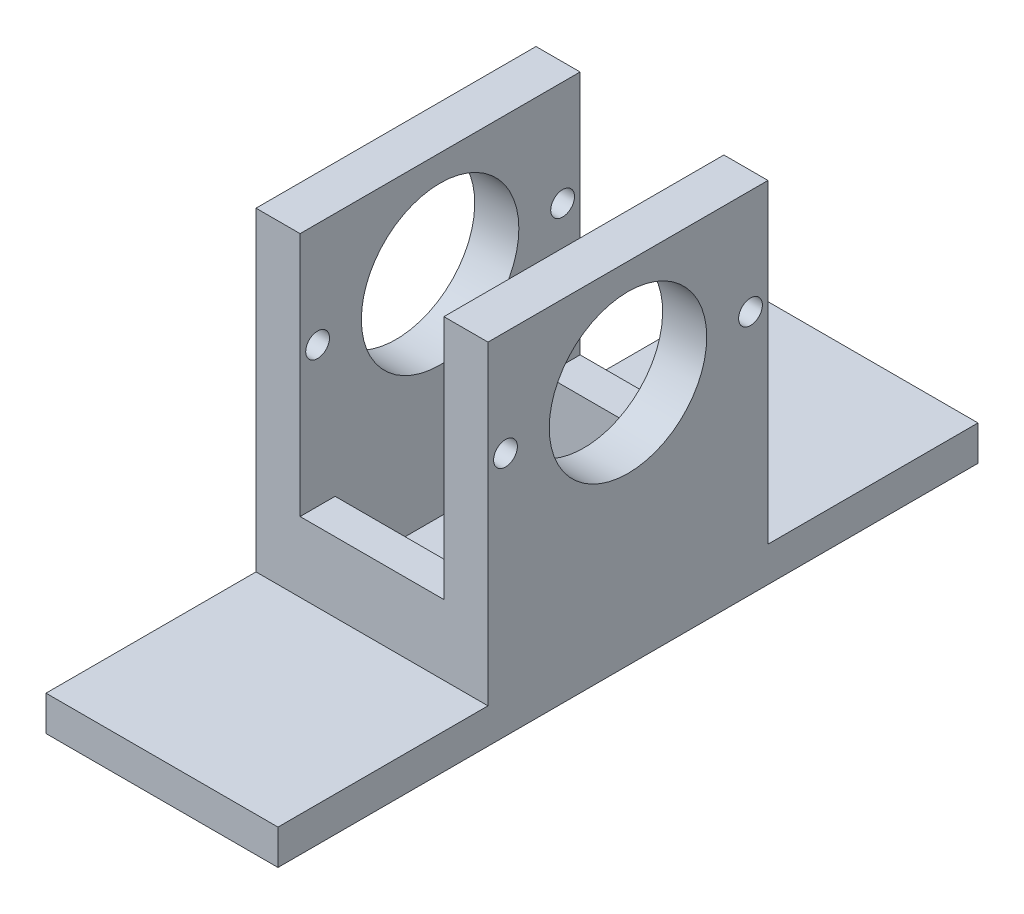
SolidWorks part; units mm, degrees
ref_plane "Front Plane" through (0, 0, 0) normal (0, 0, 1) x (1, 0, 0)
ref_plane "Top Plane" through (0, 0, 0) normal (0, 1, 0) x (1, 0, 0)
ref_plane "Right Plane" through (0, 0, 0) normal (1, 0, 0) x (0, 0, -1)
sketch "Sketch1" plane through (0, 0, 0) normal (0, 0, 1) x (1, 0, 0)
  line L0 (-21.0439, 0) -> (21.0439, 0)
  line L1 (-21.0439, 0) -> (-21.0439, 63.5)
  line L2 (21.0439, 0) -> (21.0439, 63.5)
  line L3 (-21.0439, 63.5) -> (-13.0429, 63.5)
  line L4 (-13.0429, 63.5) -> (-13.0429, 6.35)
  line L5 (-13.0429, 6.35) -> (13.0429, 6.35)
  line L6 (13.0429, 6.35) -> (13.0429, 63.5)
  line L7 (13.0429, 63.5) -> (21.0439, 63.5)
  point P3 (0, 0)
  dimension "D1" = 8.001
  dimension "D2" = 26.0858
  dimension "D3" = 6.35
  dimension "D4" = 57.15
extrude "Boss-Extrude1" add sketch "Sketch1" along normal mid plane 50.8
sketch "Sketch2" plane through (21.0439, 0, 0) normal (1, 0, 0) x (0, 0, -1)
  line L0 (-25.4, 63.5) -> (25.4, 63.5) construction
  line L1 (-25.4, 25.4) -> (25.4, 25.4) construction
  line L2 (-25.4, 25.4) -> (-25.4, 63.5) construction
  line L3 (-25.4, 63.5) -> (25.4, 63.5) construction
  line L4 (25.4, 25.4) -> (25.4, 63.5) construction
  line L5 (-25.4, 25.4) -> (25.4, 63.5) construction
  line L6 (-25.4, 63.5) -> (25.4, 25.4) construction
  line L7 (25.4, 0) -> (25.4, 63.5) construction
  line L8 (-25.4, 0) -> (-25.4, 63.5) construction
  line L9 (22.225, 44.45) -> (-22.225, 44.45) construction
  circle A0 centre (0, 44.45) radius 14.2875
  circle A1 centre (22.225, 44.45) radius 2.159
  circle A2 centre (-22.225, 44.45) radius 2.159
  point P16 (0, 44.45)
  dimension "D1" = 28.575
  dimension "D3" = 4.318
  dimension "D2" = 38.1
  dimension "D4" = 44.45
extrude "Cut-Extrude1" cut sketch "Sketch2" against normal through all both and the other way through all
sketch "Sketch3" plane through (0, 0, 0) normal (0, -1, 0) x (-1, 0, 0)
  line L0 (21.0439, -25.4) -> (21.0439, 25.4) construction
  line L1 (-21.0439, -63.5) -> (21.0439, -63.5)
  line L2 (-21.0439, -63.5) -> (-21.0439, 63.5)
  line L3 (-21.0439, 63.5) -> (21.0439, 63.5)
  line L4 (21.0439, -63.5) -> (21.0439, 63.5)
  line L5 (-21.0439, -63.5) -> (21.0439, 63.5) construction
  line L6 (-21.0439, 63.5) -> (21.0439, -63.5) construction
  line L8 (21.0439, 25.4) -> (-21.0439, 25.4) construction
  point P0 (0, 0)
  point P8 (21.0439, 0)
  point P12 (0, 25.4)
  dimension "D1" = 38.1
extrude "Boss-Extrude2" add sketch "Sketch3" against normal up to surface (6.35 mm away) contours L2 L3 L4 L1 up to face at (0, 6.35, 0)
sketch "Sketch4" plane through (0, 0, -25.4) normal (0, 0, -1) x (-1, 0, 0)
  line L0 (13.0429, 6.35) -> (13.0429, 63.5) construction
  line L1 (-13.0429, 6.35) -> (13.0429, 6.35)
  line L2 (-13.0429, 6.35) -> (-13.0429, 19.05)
  line L3 (-13.0429, 19.05) -> (13.0429, 19.05)
  line L4 (13.0429, 6.35) -> (13.0429, 19.05)
  dimension "D1" = 12.7
extrude "Boss-Extrude3" add sketch "Sketch4" against normal blind 6.35
mirror "Mirror1" about plane through (0, 0, 0) normal (0, 0, 1) of "Boss-Extrude3"
